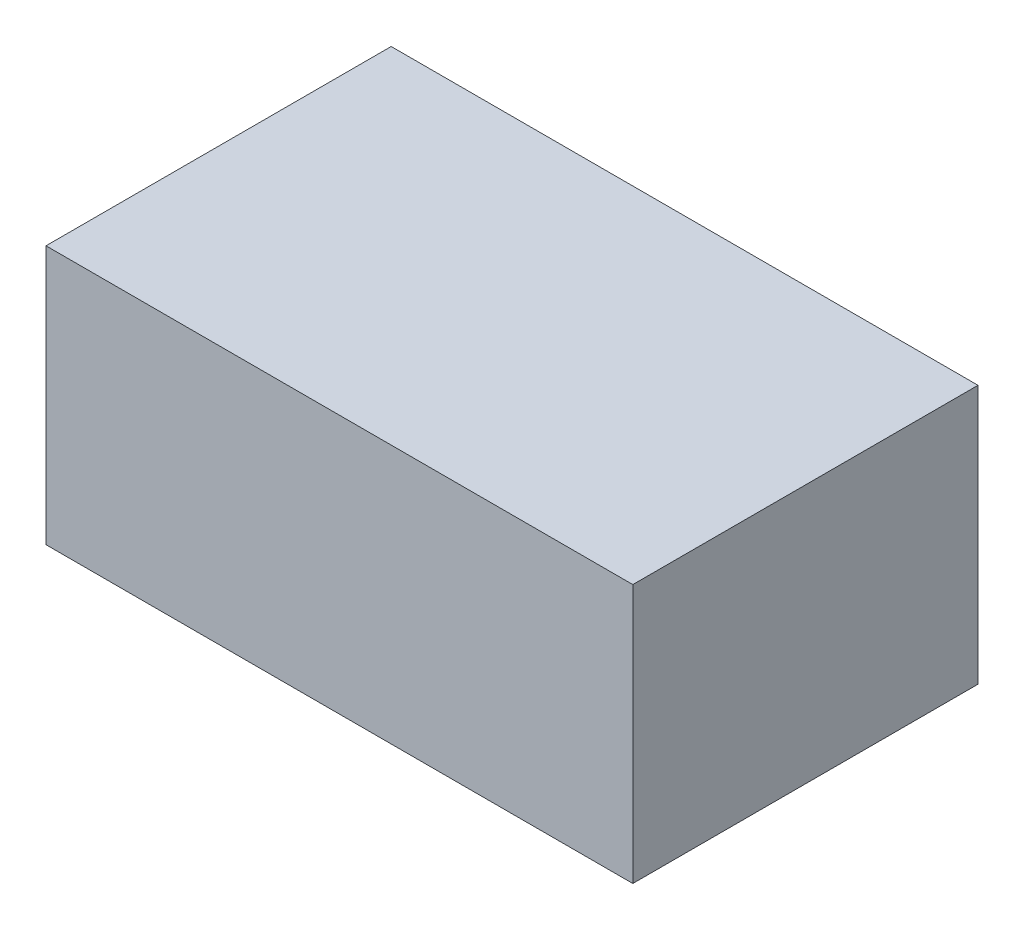
SolidWorks part; units mm, degrees
ref_plane "前视基准面" through (0, 0, 0) normal (0, 0, 1) x (1, 0, 0)
ref_plane "上视基准面" through (0, 0, 0) normal (0, 1, 0) x (1, 0, 0)
ref_plane "右视基准面" through (0, 0, 0) normal (1, 0, 0) x (0, 0, -1)
other "Configuration Table"
sketch "草图1" plane through (0, 0, 0) normal (0, 0, 1) x (1, 0, 0)
  line L1 (-34, -15) -> (34, -15)
  line L2 (-34, -15) -> (-34, 15)
  line L3 (-34, 15) -> (34, 15)
  line L4 (34, -15) -> (34, 15)
  line L5 (-34, -15) -> (34, 15) construction
  line L6 (-34, 15) -> (34, -15) construction
  point P0 (0, 0)
  dimension "D1" = 68
  dimension "D2" = 30
extrude "凸台-拉伸1" add sketch "草图1" along normal blind 40
